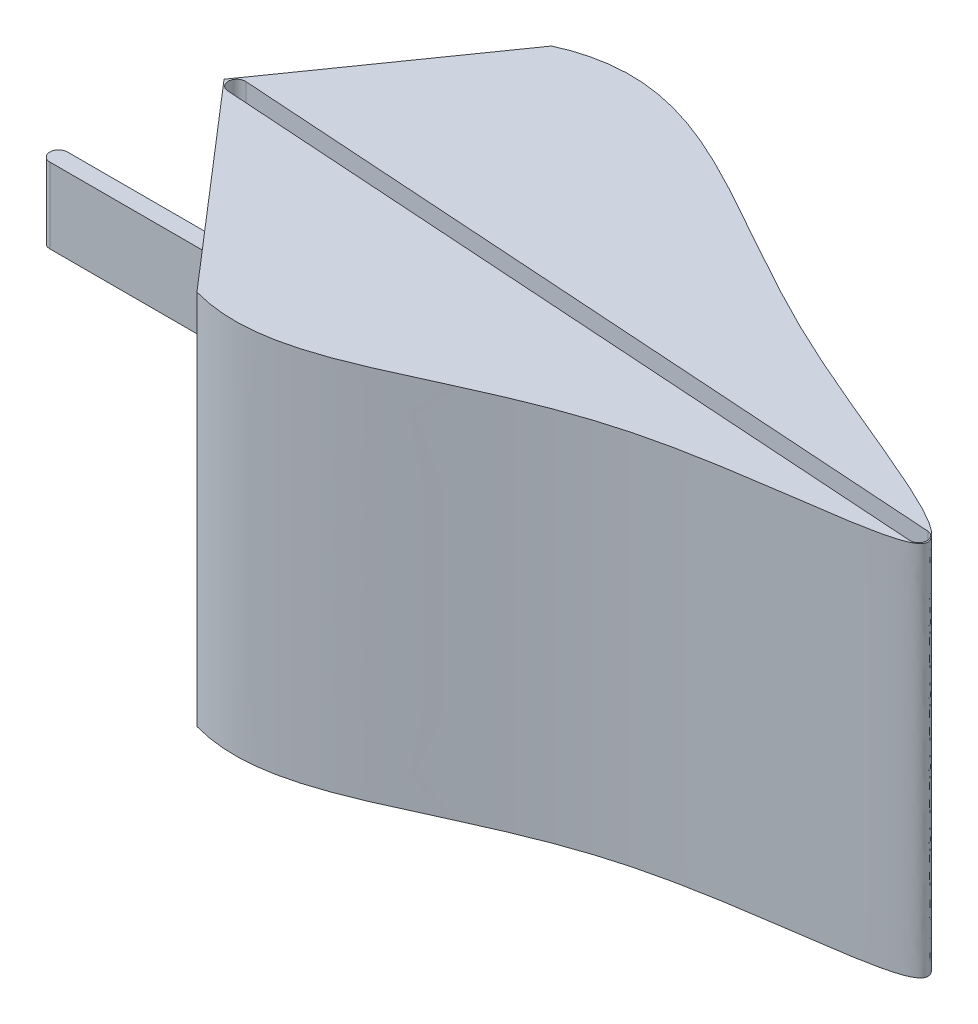
SolidWorks part; units mm, degrees
ref_plane "Front Plane" through (0, 0, 0) normal (0, 0, 1) x (1, 0, 0)
ref_plane "Top Plane" through (0, 0, 0) normal (0, 1, 0) x (1, 0, 0)
ref_plane "Right Plane" through (0, 0, 0) normal (1, 0, 0) x (0, 0, -1)
sketch "Sketch6" plane through (0, 0, 0) normal (0, 1, 0) x (1, 0, 0)
  line L0 (-1.256, 1.8414) -> (-3.0504, -0.7175)
  line L1 (-0.7806, -3.3481) -> (-3.0504, -0.7175)
  spline S0 degree 3 poles (-0.2298, -4.5968) (-4.105, -0.8652) (-0.5709, 3.2793) (2.5106, 0.3677) (8.7649, -1.6354) (2.5847, -1.7727) (-0.2298, -4.5968) (-4.105, -0.8652) (-0.5709, 3.2793) knots -0.488986 -0.346749 -0.14835 0 0.133444 0.358407 0.511014 0.653251 0.85165 1 1.133444 1.358407 1.511014 only from (-3.0504, -0.7175) to (-3.0504, -0.7175)
  dimension "D1" = 10
extrude "Boss-Extrude3" add sketch "Sketch6" along normal blind 5 contours S0 L0 L1
sketch "Sketch7" plane through (0, 5, 0) normal (0, 1, 0) x (1, 0, 0)
  line L1 (-2.8854, -0.7131) -> (6.8193, -1.3557) construction
  line L2 (-2.8779, -0.5994) -> (6.8268, -1.242)
  line L3 (-2.8929, -0.8268) -> (6.8118, -1.4694)
  arc A0 (-2.8779, -0.5994) -> (-2.8929, -0.8268) centre (-2.8854, -0.7131) ccw
  arc A1 (6.8118, -1.4694) -> (6.8268, -1.242) centre (6.8193, -1.3557) ccw
  point P0 (6.8193, -1.3557)
  point P7 (1.9669, -1.0344)
extrude "Cut-Extrude1" cut sketch "Sketch7" against normal blind 1
ref_plane "Plane1" through (0, 2.5, 0) normal (0, 1, 0) x (1, 0, 0)
sketch "Sketch9" plane through (0, 2.5, 0) normal (0, 1, 0) x (1, 0, 0)
  line L0 (-2.9858, -0.7119) -> (-5.2543, -0.7119) construction
  line L3 (-2.9858, -0.8283) -> (-5.2543, -0.8283)
  line L4 (-2.9858, -0.5955) -> (-5.2543, -0.5955)
  arc A2 (-2.9858, -0.8283) -> (-2.9858, -0.5955) centre (-2.9858, -0.7119) ccw
  arc A3 (-5.2543, -0.5955) -> (-5.2543, -0.8283) centre (-5.2543, -0.7119) ccw
  point P3 (-4.1201, -0.7119)
extrude "Boss-Extrude5" add sketch "Sketch9" along normal blind 0.5 and the other way blind 0.5
